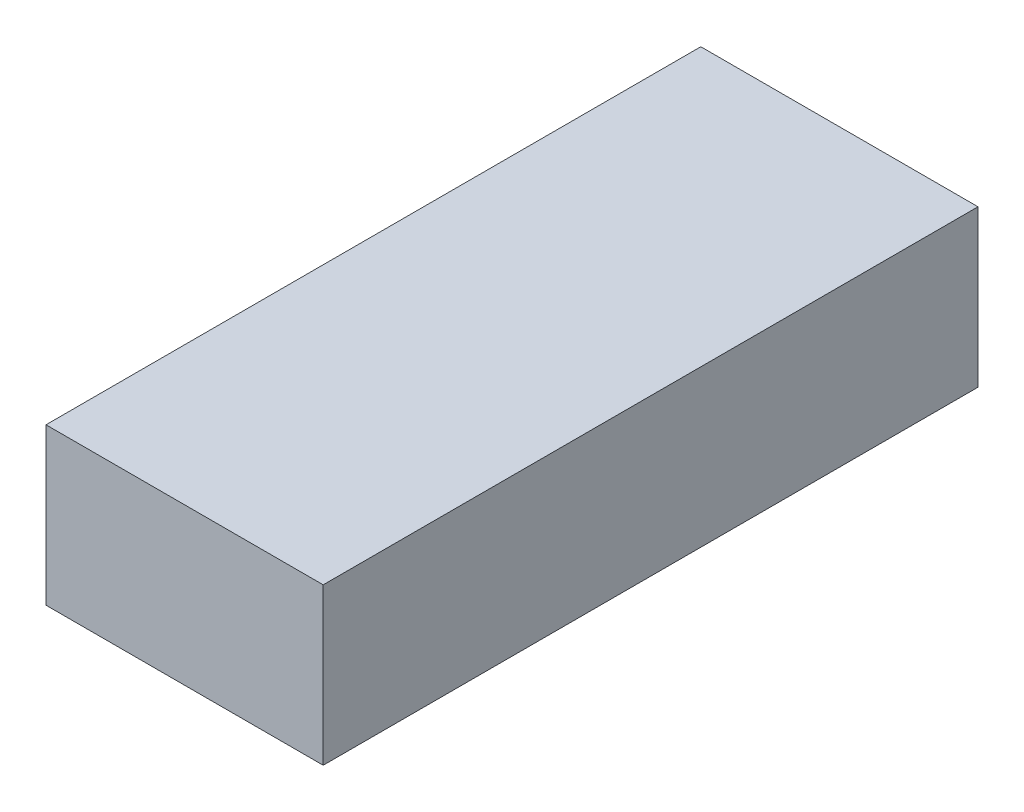
SolidWorks part; units mm, degrees
ref_plane "Plano frontal" through (0, 0, 0) normal (0, 0, 1) x (1, 0, 0)
ref_plane "Plano superior" through (0, 0, 0) normal (0, 1, 0) x (1, 0, 0)
ref_plane "Plano direito" through (0, 0, 0) normal (1, 0, 0) x (0, 0, -1)
sketch "Esboço1" plane through (0, 0, 0) normal (0, 0, 1) x (1, 0, 0)
  line L1 (-3.175, -1.79) -> (3.175, -1.79)
  line L2 (-3.175, -1.79) -> (-3.175, 1.79)
  line L3 (-3.175, 1.79) -> (3.175, 1.79)
  line L4 (3.175, -1.79) -> (3.175, 1.79)
  point P5 (-3.3863, -1.6198)
  point P6 (0, 1.79)
  point P8 (3.175, 0)
  dimension "D1" = 3.58
  dimension "D2" = 6.35
extrude "Ressalto-extrusão1" add sketch "Esboço1" along normal blind 15
